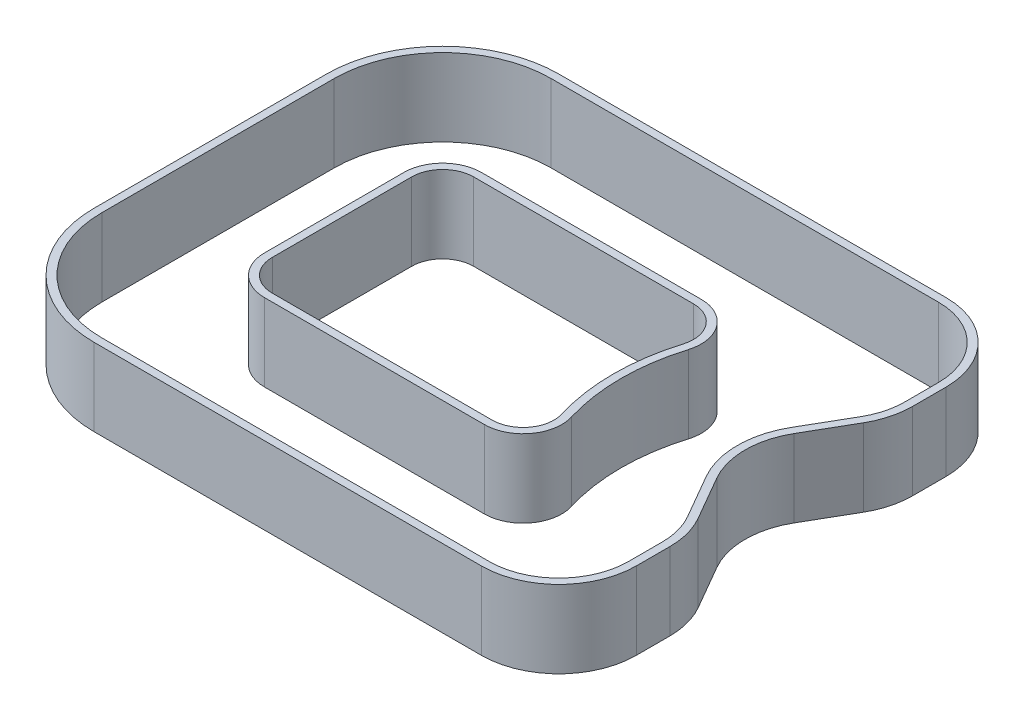
SolidWorks part; units mm, degrees
material "ABS"
ref_plane "前视基准面" through (0, 0, 0) normal (0, 0, 1) x (1, 0, 0)
ref_plane "上视基准面" through (0, 0, 0) normal (0, 1, 0) x (1, 0, 0)
ref_plane "右视基准面" through (0, 0, 0) normal (1, 0, 0) x (0, 0, -1)
sketch "草图2" plane through (0, 0, 0) normal (0, 1, 0) x (1, 0, 0)
  line L0 (150, 60) -> (102.001, 60) construction
  line L1 (30, 0) -> (130, 0)
  line L2 (0, 30) -> (0, 90)
  line L3 (30, 120) -> (130, 120)
  line L4 (150, 0) -> (150, 120) construction
  line L5 (140.7735, 70) -> (147.3205, 81.3397)
  line L6 (140.7735, 50) -> (147.3205, 38.6603)
  line L7 (150, 100) -> (150, 91.3397)
  line L8 (150, 28.6603) -> (150, 20)
  line L9 (30, 118) -> (130, 118)
  line L10 (148, 100) -> (148, 91.3397)
  line L11 (139.0415, 71) -> (145.5885, 82.3397)
  line L12 (139.0415, 49) -> (145.5885, 37.6603)
  line L13 (148, 28.6603) -> (148, 20)
  line L14 (30, 2) -> (130, 2)
  line L15 (2, 30) -> (2, 90)
  line L16 (42, 88) -> (98.7644, 88)
  line L17 (114.2154, 88) -> (114.2154, 88)
  line L18 (113.0607, 86) -> (114.2154, 88)
  line L19 (113.0607, 34) -> (114.2154, 32)
  line L20 (114.2154, 32) -> (114.2154, 32)
  line L21 (42, 32) -> (98.7644, 32)
  line L22 (32, 42) -> (32, 78)
  line L23 (32, 88) -> (114.2154, 88) construction
  line L24 (32, 32) -> (114.2154, 32) construction
  line L25 (32, 32) -> (32, 88) construction
  line L26 (42, 86) -> (98.7644, 86)
  line L27 (42, 34) -> (98.7644, 34)
  line L28 (34, 42) -> (34, 78)
  arc A0 (0, 90) -> (30, 120) centre (30, 90) cw
  arc A1 (150, 100) -> (130, 120) centre (130, 100) ccw
  arc A2 (150, 91.3397) -> (147.3205, 81.3397) centre (130, 91.3397) cw
  arc A3 (130, 0) -> (150, 20) centre (130, 20) ccw
  arc A4 (147.3205, 38.6603) -> (150, 28.6603) centre (130, 28.6603) cw
  arc A5 (140.7735, 50) -> (140.7735, 70) centre (158.094, 60) cw
  arc A6 (30, 0) -> (0, 30) centre (30, 30) cw
  arc A7 (148, 100) -> (130, 118) centre (130, 100) ccw
  arc A8 (148, 91.3397) -> (145.5885, 82.3397) centre (130, 91.3397) cw
  arc A9 (139.0415, 49) -> (139.0415, 71) centre (158.094, 60) cw
  arc A10 (145.5885, 37.6603) -> (148, 28.6603) centre (130, 28.6603) cw
  arc A11 (130, 2) -> (148, 20) centre (130, 20) ccw
  arc A12 (30, 2) -> (2, 30) centre (30, 30) cw
  arc A13 (2, 90) -> (30, 118) centre (30, 90) cw
  arc A14 (114.2154, 88) -> (114.2154, 88) centre (114.2154, 88) ccw
  arc A15 (114.2154, 88) -> (114.2154, 88) centre (114.2154, 88) cw
  arc A16 (108.3337, 44.9032) -> (108.3337, 75.0968) centre (158.094, 60) cw
  arc A17 (114.2154, 32) -> (114.2154, 32) centre (114.2154, 32) cw
  arc A18 (114.2154, 32) -> (114.2154, 32) centre (114.2154, 32) ccw
  arc A21 (113.0607, 34) -> (113.0607, 86) centre (158.094, 60) cw construction
  arc A22 (98.7644, 88) -> (108.3337, 75.0968) centre (98.7644, 78) cw
  arc A23 (108.3337, 44.9032) -> (98.7644, 32) centre (98.7644, 42) cw
  arc A24 (42, 32) -> (32, 42) centre (42, 42) cw
  arc A25 (32, 32) -> (32, 32) centre (32, 32) cw construction
  arc A26 (32, 78) -> (42, 88) centre (42, 78) cw
  arc A27 (32, 88) -> (32, 88) centre (32, 88) cw construction
  arc A28 (98.7644, 86) -> (106.4199, 75.6774) centre (98.7644, 78) cw
  arc A29 (106.4199, 44.3226) -> (106.4199, 75.6774) centre (158.094, 60) cw
  arc A30 (106.4199, 44.3226) -> (98.7644, 34) centre (98.7644, 42) cw
  arc A31 (42, 34) -> (34, 42) centre (42, 42) cw
  arc A32 (34, 78) -> (42, 86) centre (42, 78) cw
  point P7 (0, 120)
  point P18 (150, 85.9808)
  point P24 (150, 34.0192)
  point P27 (135, 60)
  point P30 (0, 0)
  dimension "D3" = 30
  dimension "D6" = 20
  dimension "D7" = 20
  dimension "D8" = 20
  dimension "D9" = 30
  dimension "D12" = 10
  dimension "D1" = 150
  dimension "D2" = 120
  dimension "D4" = 60
  dimension "D5" = 30
  dimension "D10" = 2
  dimension "D11" = 32
  dimension "D13" = 2
extrude "凸台-拉伸2" add sketch "草图2" along normal blind 20 contours A6 L1 A3 L8 A4 L6 A5 L5 A2 L7 A1 L3 A0 L2 L15 A13 L9 A7 L10 A8 L11 A9 L12 A10 L13 A11 L14 A12 | A26 L22 A24 L21 A23 A16 A22 L16 L28 A32 L26 A28 A29 A30 L27 A31
sketch "草图3" plane through (0, 0, 0) normal (0, -1, 0) x (1, 0, 0)
  line L0 (0, -30) -> (0, -90) construction
  line L1 (30, -120) -> (130, -120) construction
  line L2 (150, -100) -> (150, -91.3397) construction
  line L3 (140.7735, -70) -> (147.3205, -81.3397) construction
  line L4 (140.7735, -50) -> (147.3205, -38.6603) construction
  line L5 (150, -28.6603) -> (150, -20) construction
  line L6 (30, 0) -> (130, 0) construction
  line L7 (0, -30) -> (0, -90)
  line L8 (30, -120) -> (130, -120)
  line L9 (150, -100) -> (150, -91.3397)
  line L10 (140.7735, -70) -> (147.3205, -81.3397)
  line L11 (140.7735, -50) -> (147.3205, -38.6603)
  line L12 (150, -28.6603) -> (150, -20)
  line L13 (30, 0) -> (130, 0)
  arc A0 (0, -90) -> (30, -120) centre (30, -90) ccw construction
  arc A1 (130, -120) -> (150, -100) centre (130, -100) ccw construction
  arc A2 (150, -91.3397) -> (147.3205, -81.3397) centre (130, -91.3397) ccw construction
  arc A3 (140.7735, -50) -> (140.7735, -70) centre (158.094, -60) ccw construction
  arc A4 (147.3205, -38.6603) -> (150, -28.6603) centre (130, -28.6603) ccw construction
  arc A5 (150, -20) -> (130, 0) centre (130, -20) ccw construction
  arc A6 (30, 0) -> (0, -30) centre (30, -30) ccw construction
  arc A7 (0, -90) -> (30, -120) centre (30, -90) ccw
  arc A8 (130, -120) -> (150, -100) centre (130, -100) ccw
  arc A9 (150, -91.3397) -> (147.3205, -81.3397) centre (130, -91.3397) ccw
  arc A10 (140.7735, -50) -> (140.7735, -70) centre (158.094, -60) ccw
  arc A11 (147.3205, -38.6603) -> (150, -28.6603) centre (130, -28.6603) ccw
  arc A12 (150, -20) -> (130, 0) centre (130, -20) ccw
  arc A13 (30, 0) -> (0, -30) centre (30, -30) ccw
